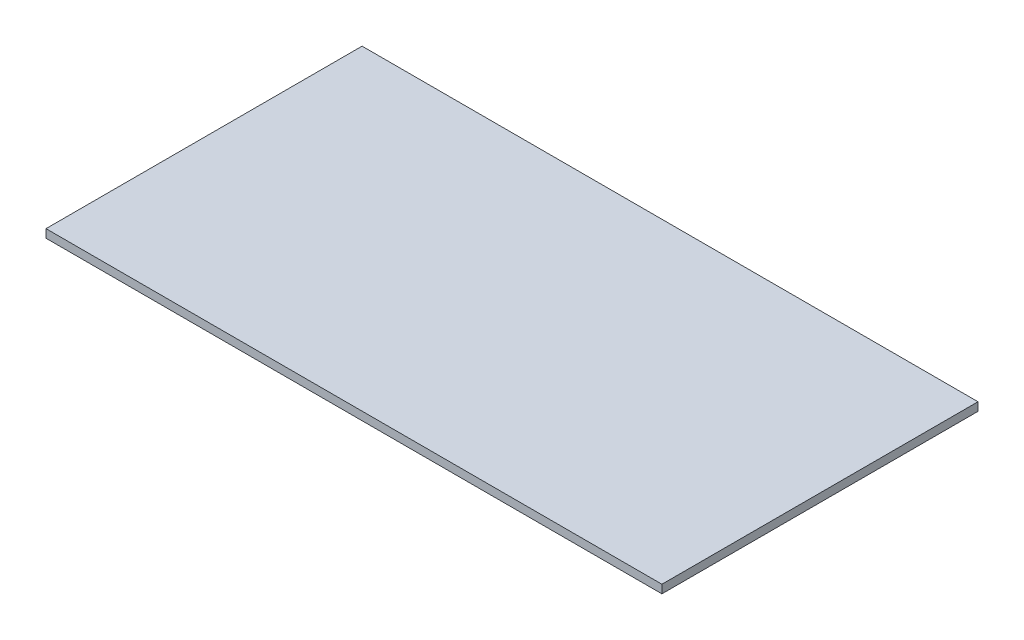
SolidWorks part; units mm, degrees
ref_plane "Front Plane" through (0, 0, 0) normal (0, 0, 1) x (1, 0, 0)
ref_plane "Top Plane" through (0, 0, 0) normal (0, 1, 0) x (1, 0, 0)
ref_plane "Right Plane" through (0, 0, 0) normal (1, 0, 0) x (0, 0, -1)
sketch "Sketch1" plane through (0, 0, 0) normal (0, 1, 0) x (1, 0, 0)
  line L5 (-73.85, 37.9) -> (73.85, 37.9)
  line L6 (-73.85, 37.9) -> (-73.85, -37.9)
  line L7 (-73.85, -37.9) -> (73.85, -37.9)
  line L8 (73.85, 37.9) -> (73.85, -37.9)
  line L9 (-73.85, 37.9) -> (73.85, -37.9) construction
  line L10 (-73.85, -37.9) -> (73.85, 37.9) construction
  point P0 (0, 0)
  dimension "D1" = 147.7
  dimension "D2" = 75.8
extrude "Boss-Extrude1" add sketch "Sketch1" along normal blind 2
